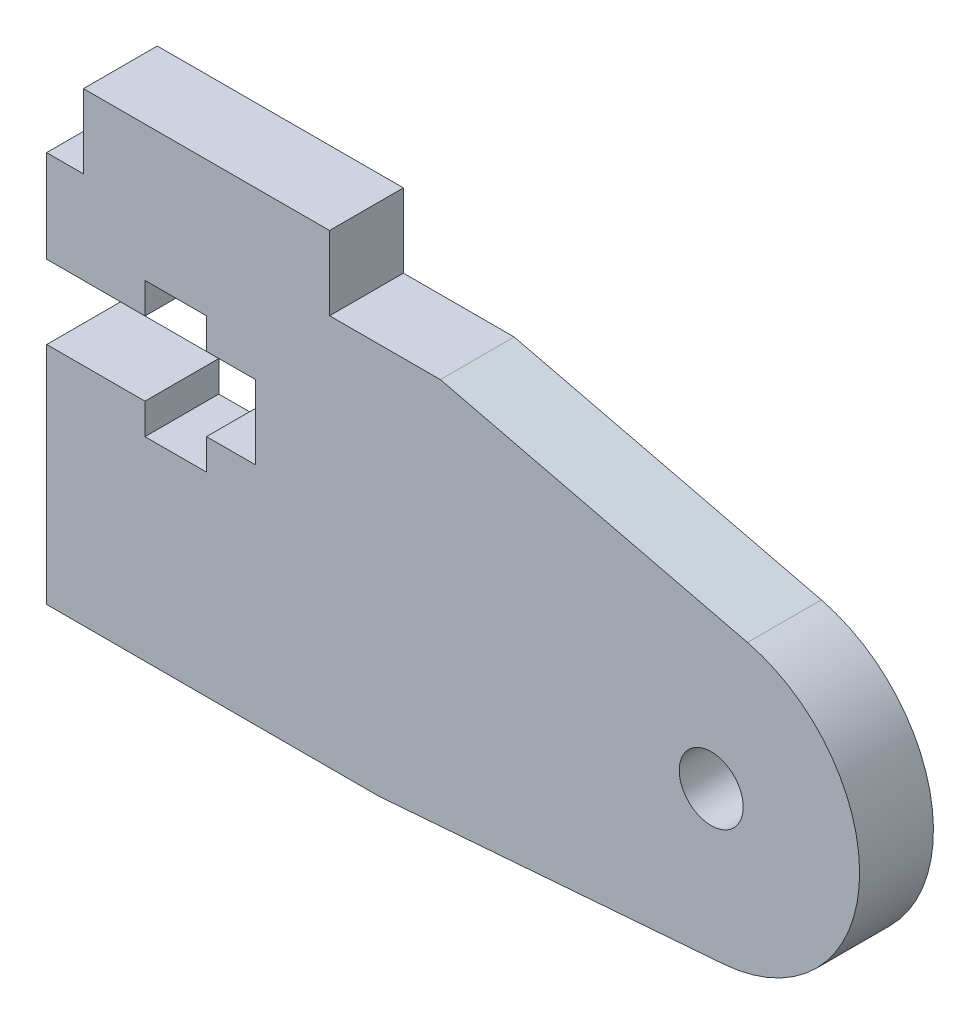
SolidWorks part; units mm, degrees
ref_plane "前基準面" through (0, 0, 0) normal (0, 0, 1) x (1, 0, 0)
ref_plane "上基準面" through (0, 0, 0) normal (0, 1, 0) x (1, 0, 0)
ref_plane "右基準面" through (0, 0, 0) normal (1, 0, 0) x (0, 0, -1)
sketch "草圖1" plane through (0, 0, 0) normal (0, 0, 1) x (1, 0, 0)
  line L0 (216.4926, 78.2341) -> (216.4936, 76.9841) construction
  line L1 (218.4926, 78.2357) -> (216.4926, 78.2341) construction
  line L2 (218.4903, 81.2357) -> (218.4926, 78.2357) construction
  line L3 (216.4903, 81.2341) -> (218.4903, 81.2357) construction
  line L4 (216.4893, 82.4841) -> (216.4903, 81.2341) construction
  line L5 (213.9967, 82.4821) -> (216.4893, 82.4841) construction
  line L6 (213.9977, 81.2321) -> (213.9967, 82.4821) construction
  line L7 (209.9977, 81.229) -> (213.9977, 81.2321) construction
  line L8 (213.9936, 76.9821) -> (213.9926, 78.2321) construction
  line L9 (216.4936, 76.9841) -> (213.9936, 76.9821) construction
  line L10 (213.9926, 78.2321) -> (210.0001, 78.229) construction
  line L11 (209.9999, 69.08) -> (223.4882, 69.08) construction
  line L12 (223.4882, 69.08) -> (237.5179, 70.1788) construction
  line L13 (238.4772, 81.9825) -> (225.9948, 84.9915) construction
  line L14 (225.9948, 84.9915) -> (221.4948, 84.988) construction
  line L15 (221.4948, 84.988) -> (221.4924, 87.988) construction
  line L16 (211.4948, 84.9801) -> (211.4924, 87.9801) construction
  line L17 (209.9948, 84.9789) -> (211.4948, 84.9801) construction
  line L18 (216.4926, 78.2341) -> (216.4936, 76.9841)
  line L19 (218.4926, 78.2357) -> (216.4926, 78.2341)
  line L20 (218.4903, 81.2357) -> (218.4926, 78.2357)
  line L21 (216.4903, 81.2341) -> (218.4903, 81.2357)
  line L22 (216.4893, 82.4841) -> (216.4903, 81.2341)
  line L23 (213.9967, 82.4821) -> (216.4893, 82.4841)
  line L24 (213.9977, 81.2321) -> (213.9967, 82.4821)
  line L25 (209.9977, 81.229) -> (213.9977, 81.2321)
  line L26 (213.9936, 76.9821) -> (213.9926, 78.2321)
  line L27 (216.4936, 76.9841) -> (213.9936, 76.9821)
  line L28 (213.9926, 78.2321) -> (210.0001, 78.229)
  line L29 (209.9999, 69.08) -> (223.4882, 69.08)
  line L30 (223.4882, 69.08) -> (237.5179, 70.1788)
  line L31 (238.4772, 81.9825) -> (225.9948, 84.9915)
  line L32 (225.9948, 84.9915) -> (221.4948, 84.988)
  line L33 (221.4948, 84.988) -> (221.4924, 87.988)
  line L34 (211.4948, 84.9801) -> (211.4924, 87.9801)
  line L35 (209.9948, 84.9789) -> (211.4948, 84.9801)
  line L36 (210.0001, 78.229) -> (209.9999, 69.08)
  line L37 (209.9977, 81.229) -> (209.9948, 84.9789)
  line L38 (211.4924, 87.9801) -> (221.4924, 87.988)
  circle A0 centre (237.0018, 76.1002) radius 1.3 construction
  circle A1 centre (237.0018, 76.1002) radius 1.3
  arc A2 (238.4772, 81.9825) -> (237.5179, 70.1788) centre (237.0321, 76.1591) cw
extrude "填料-伸長1" add sketch "草圖1" along normal blind 3
